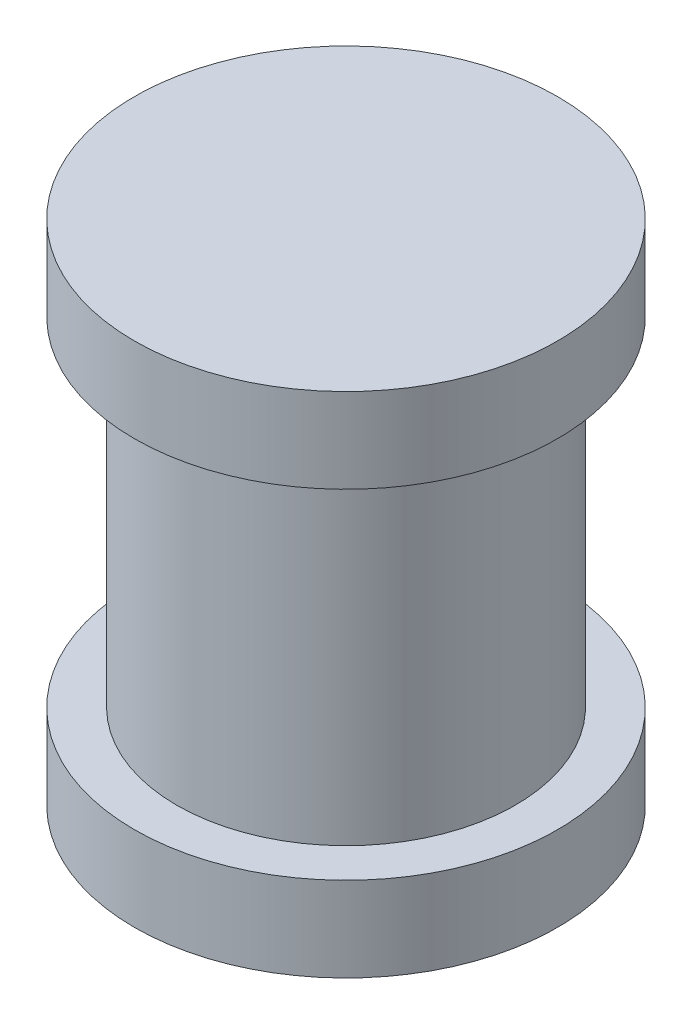
SolidWorks part; units mm, degrees
ref_plane "Front Plane" through (0, 0, 0) normal (0, 0, 1) x (1, 0, 0)
ref_plane "Top Plane" through (0, 0, 0) normal (0, 1, 0) x (1, 0, 0)
ref_plane "Right Plane" through (0, 0, 0) normal (1, 0, 0) x (0, 0, -1)
sketch "Sketch1" plane through (0, 0, 0) normal (0, 1, 0) x (1, 0, 0)
  circle A0 centre (0, 0) radius 0.5
  dimension "D1" = 1
extrude "Boss-Extrude1" add sketch "Sketch1" along normal blind 1
sketch "Sketch2" plane through (0, 0, 0) normal (0, 1, 0) x (1, 0, 0)
  circle A0 centre (0, 0) radius 0.625
  dimension "D1" = 1.25
extrude "Boss-Extrude2" add sketch "Sketch2" against normal blind 0.25
sketch "Sketch3" plane through (0, 1, 0) normal (0, 1, 0) x (1, 0, 0)
  circle A0 centre (0, 0) radius 0.625
extrude "Boss-Extrude3" add sketch "Sketch3" along normal blind 0.25
